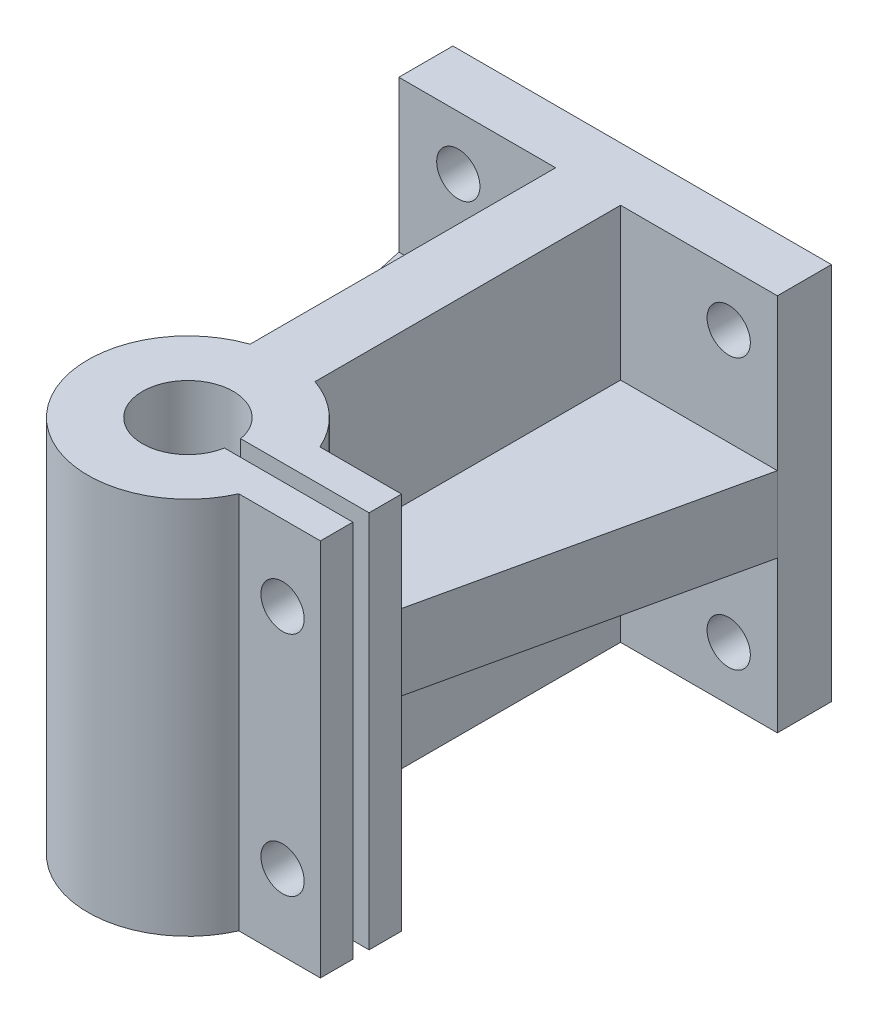
SolidWorks part; units mm, degrees
ref_plane "Płaszczyzna przednia" through (0, 0, 0) normal (0, 0, 1) x (1, 0, 0)
ref_plane "Płaszczyzna górna" through (0, 0, 0) normal (0, 1, 0) x (1, 0, 0)
ref_plane "Płaszczyzna prawa" through (0, 0, 0) normal (1, 0, 0) x (0, 0, -1)
sketch "Szkic2" plane through (0, 0, 0) normal (0, 1, 0) x (1, 0, 0)
  line L1 (-17.5, 0) -> (17.5, 0)
  line L2 (-17.5, 0) -> (-17.5, 5)
  line L3 (-17.5, 5) -> (17.5, 5)
  line L4 (17.5, 0) -> (17.5, 5)
extrude "Dodanie-wyciągnięcie1" add sketch "Szkic2" along normal blind 35
sketch "Szkic3" plane through (0, 0, 0) normal (0, -1, 0) x (1, 0, 0)
  circle A0 centre (0, 37) radius 4.2
  circle A1 centre (0, 37) radius 9.25
  point P2 (0, 0)
extrude "Dodanie-wyciągnięcie2" add sketch "Szkic3" against normal blind 35 separate body
sketch "Szkic4" plane through (0, 0, 0) normal (0, -1, 0) x (1, 0, 0)
  line L0 (-17.5, 0) -> (17.5, 0) construction
  line L1 (-3, 0) -> (3, 0)
  line L2 (-3, 0) -> (-3, 30.7103)
  line L3 (-3, 30.7103) -> (3, 30.7103)
  line L4 (3, 0) -> (3, 30.7103)
  point P6 (0, 0)
extrude "Dodanie-wyciągnięcie3" add sketch "Szkic4" against normal blind 35
sketch "Szkic5" plane through (0, 0, 0) normal (0, -1, 0) x (1, 0, 0)
  line L0 (0, 0) -> (-17.5, 0)
  line L1 (-17.5, 0) -> (-9.25, 37)
  line L2 (-9.25, 37) -> (-3, 28.25)
  line L3 (-3, 28.25) -> (-3, 0) construction
  line L4 (-3, 28.25) -> (0, 0)
  line L5 (3, 0) -> (3, 28.25)
  line L6 (3, 28.25) -> (9.25, 37)
  line L7 (9.25, 37) -> (17.5, 0)
  line L8 (17.5, 0) -> (3, 0)
  circle A0 centre (0, 37) radius 9.25 construction
  point P7 (-9.25, 37)
  point P8 (9.25, 37)
  point P19 (0, 0)
extrude "Dodanie-wyciągnięcie4" add sketch "Szkic5" against normal blind 7 from offset 14 offset against normal yes
sketch "Szkic7" plane through (0, 0, -5) normal (0, 0, -1) x (-1, 0, 0)
  circle A0 centre (-13, 30) radius 2
  circle A1 centre (12, 30) radius 2
  circle A2 centre (12, 5) radius 2
  circle A3 centre (-13, 5) radius 2
  point P8 (0, 0)
  point P9 (0, 0)
  point P10 (0, 0)
  point P11 (0, 0)
  point P12 (0, 0)
  point P13 (0, 0)
  point P14 (0, 0)
  point P15 (0, 0)
extrude "Wytnij-wyciągnięcie1" cut sketch "Szkic7" against normal up to next
sketch "Szkic8" plane through (0, 0, 0) normal (0, -1, 0) x (1, 0, 0)
  line L1 (4.1325, 37.75) -> (14.7704, 37.75)
  line L2 (4.1325, 37.75) -> (4.1325, 36.25)
  line L3 (4.1325, 36.25) -> (14.7704, 36.25)
  line L4 (14.7704, 37.75) -> (14.7704, 36.25)
  circle A0 centre (0, 37) radius 4.2 construction
  point P6 (0, 0)
  point P7 (0, 0)
  point P8 (0, 0)
  point P9 (0, 0)
  point P10 (0, 0)
  point P11 (0, 0)
  point P12 (0, 0)
  point P13 (0, 0)
extrude "Wytnij-wyciągnięcie2" cut sketch "Szkic8" against normal up to next
sketch "Szkic11" plane through (0, 0, 0) normal (0, -1, 0) x (-1, 0, 0)
  line L0 (-4.1325, -36.25) -> (-9.2195, -36.25) construction
  line L1 (-6.3275, -36.25) -> (-16, -36.25)
  line L2 (-6.3275, -36.25) -> (-6.3275, -33.25)
  line L3 (-6.3275, -33.25) -> (-16, -33.25)
  line L4 (-16, -36.25) -> (-16, -33.25)
  line L5 (-9.2195, -37.75) -> (-4.1325, -37.75) construction
  line L6 (-6.3275, -37.75) -> (-16, -37.75)
  line L7 (-6.3275, -37.75) -> (-6.3275, -40.75)
  line L8 (-6.3275, -40.75) -> (-16, -40.75)
  line L9 (-16, -37.75) -> (-16, -40.75)
  point P12 (0, 0)
  point P13 (0, 0)
  point P14 (0, 0)
extrude "Dodanie-wyciągnięcie6" add sketch "Szkic11" against normal blind 35
sketch "Szkic12" plane through (0, 0, 40.75) normal (0, 0, 1) x (1, 0, 0)
  circle A0 centre (12.5, 28) radius 2
  circle A1 centre (12.5, 7) radius 2
extrude "Wytnij-wyciągnięcie4" cut sketch "Szkic12" against normal blind 12
